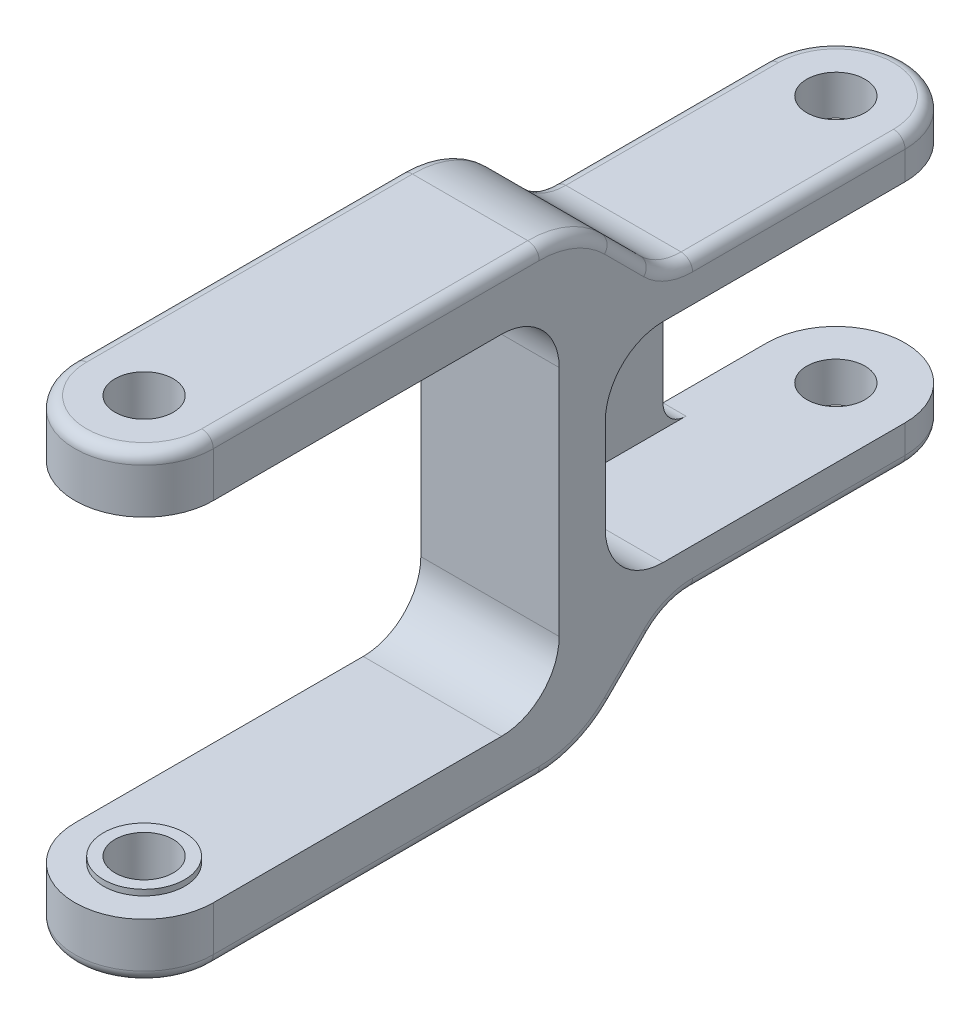
SolidWorks part; units mm, degrees
ref_plane "前视基准面" through (0, 0, 0) normal (0, 0, 1) x (1, 0, 0)
ref_plane "上视基准面" through (0, 0, 0) normal (0, 1, 0) x (1, 0, 0)
ref_plane "右视基准面" through (0, 0, 0) normal (1, 0, 0) x (0, 0, -1)
other "Configuration Table"
sketch "草图1" plane through (0, 0, 0) normal (0, 1, 0) x (1, 0, 0)
  line L0 (0, 0) -> (0, 60) construction
  line L1 (-6, 0) -> (-6, 60)
  line L2 (6, 0) -> (6, 60)
  arc A0 (-6, 0) -> (6, 0) centre (0, 0) ccw
  arc A1 (6, 60) -> (-6, 60) centre (0, 60) ccw
  circle A2 centre (0, 60) radius 2.525
  circle A3 centre (0, 0) radius 2.525
  point P3 (0, 30)
  dimension "D3" = 5.05
  dimension "D4" = 5.05
  dimension "D1" = 12
  dimension "D2" = 60
extrude "凸台-拉伸1" add sketch "草图1" along normal mid plane 40
sketch "草图2" plane through (-6, 0, 0) normal (-1, 0, 0) x (0, 0, 1)
  line L0 (-90.5978, 0) -> (35.7902, 0) construction
  line L1 (6, -20) -> (6, 20) construction
  line L2 (-30, 15.1) -> (6, 15.1)
  line L3 (-30, 15.1) -> (-30, -15.1)
  line L4 (-30, -15.1) -> (6, -15.1)
  line L5 (6, 15.1) -> (6, -15.1)
  line L6 (0, 20) -> (0, -20) construction
  line L7 (-60, 20) -> (0, 20) construction
  line L8 (-66, 20) -> (-66, -20) construction
  line L9 (-66, 9.05) -> (-49, 9.05)
  line L10 (-66, 9.05) -> (-66, -9.05)
  line L11 (-66, -9.05) -> (-49, -9.05)
  line L12 (-49, 9.05) -> (-49, -9.05)
  line L13 (-32, 20) -> (-39.5, 12.5)
  line L14 (-39.5, 12.5) -> (-66, 12.5)
  line L15 (-66, 12.5) -> (-66, 20)
  line L16 (-66, 20) -> (-32, 20)
  line L17 (-66, -12.5) -> (-66, -20)
  line L18 (-39.5, -12.5) -> (-66, -12.5)
  line L19 (-32, -20) -> (-39.5, -12.5)
  line L20 (-66, -20) -> (-32, -20)
  dimension "D1" = 30
  dimension "D2" = 15.1
  dimension "D3" = 17
  dimension "D4" = 9.05
  dimension "D5" = 45
  dimension "D6" = 7.5
  dimension "D7" = 2
extrude "切除-拉伸1" cut sketch "草图2" against normal blind 28
sketch "草图3" plane through (6, 0, 0) normal (1, 0, 0) x (0, 0, -1)
  line L0 (60, -9.05) -> (49, -9.05) construction
  line L1 (49, 9.05) -> (34, 9.05)
  line L2 (49, 9.05) -> (49, -9.05)
  line L3 (49, -9.05) -> (34, -9.05)
  line L4 (34, 9.05) -> (34, -9.05)
  dimension "D1" = 15
extrude "切除-拉伸2" cut sketch "草图3" against normal blind 10
fillet "圆角2" radius 9 2 edges at (0, 20, -32) (0, -20, -32)
fillet "圆角3" radius 5 2 edges at (0, 12.5, -39.5) (0, -12.5, -39.5)
fillet "圆角4" radius 5 2 edges at (0, 15.1, -30) (0, -15.1, -30)
fillet "圆角5" radius 5 2 edges at (1, 9.05, -34) (1, -9.05, -34)
fillet "圆角6" radius 2 2 edges at (-5, -9.05, -49) (-5, 9.05, -49)
fillet "圆角7" radius 1 24 edges at (-6, -19.3149, -31.7162) (-6, -12.8806, -39.6577) (-6, -12.5, -50.7855) (0, -12.5, -66) (6, -12.5, -50.7855) (6, -12.8806, -39.6577) (6, -19.3149, -31.7162) (6, -20, -14.136) (0, -20, 6) (-6, 19.3149, -31.7162) (-6, 12.8806, -39.6577) (-6, 12.5, -50.7855) (0, 12.5, -66) (6, 12.5, -50.7855) (6, 12.8806, -39.6577) (6, 19.3149, -31.7162) (6, 20, -14.136) (0, 20, 6) (-6, -20, -14.136) (-6, 20, -14.136) (-6, -15.6642, -36.3358) (6, -15.6642, -36.3358) (-6, 15.6642, -36.3358) (6, 15.6642, -36.3358)
sketch "草图4" plane through (0, 15.1, 0) normal (0, -1, 0) x (1, 0, 0)
  circle A0 centre (0, 0) radius 3.525
  circle A1 centre (0, 0) radius 2.525 construction
  circle A2 centre (0, 0) radius 2.525
  dimension "D1" = 1
extrude "凸台-拉伸2" add sketch "草图4" along normal blind 0.5
ref_plane "基准面1" through (0, 0, 0) normal (0, -1, 0) x (-1, 0, 0)
mirror "镜向1" about plane through (0, 0, 0) normal (0, -1, 0) of "凸台-拉伸2"
